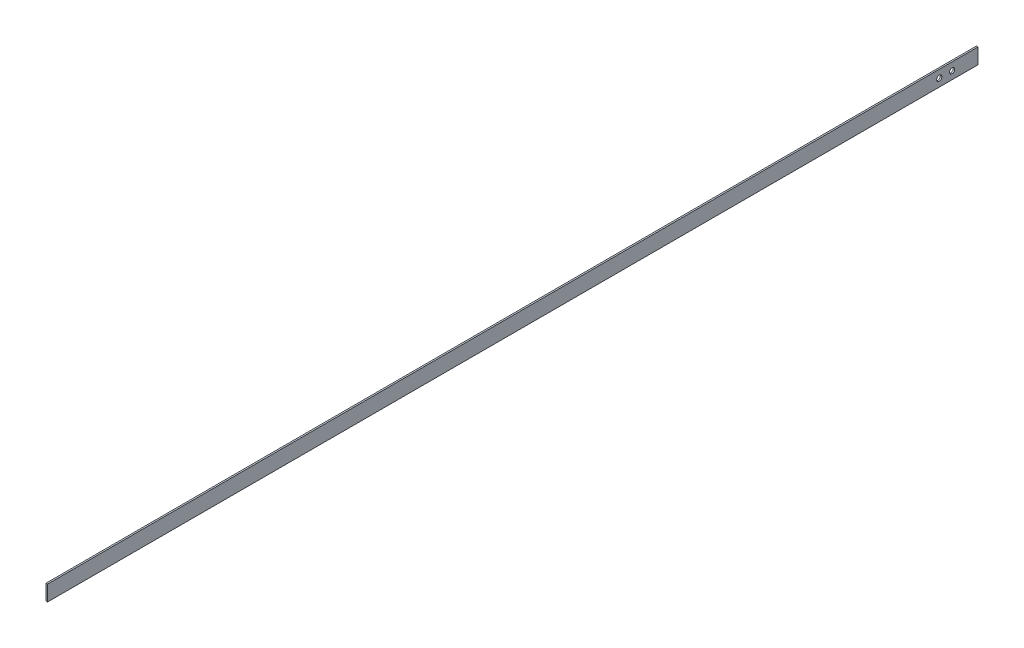
SolidWorks part; units mm, degrees
material "Bellirium COpper"
ref_plane "Front Plane" through (0, 0, 0) normal (0, 0, 1) x (1, 0, 0)
ref_plane "Top Plane" through (0, 0, 0) normal (0, 1, 0) x (1, 0, 0)
ref_plane "Right Plane" through (0, 0, 0) normal (1, 0, 0) x (0, 0, -1)
sketch "Sketch1" plane through (0, 0, 0) normal (0, 0, 1) x (1, 0, 0)
  line L1 (-0.15, -1.5) -> (0.15, -1.5)
  line L2 (-0.15, -1.5) -> (-0.15, 1.5)
  line L3 (-0.15, 1.5) -> (0.15, 1.5)
  line L4 (0.15, -1.5) -> (0.15, 1.5)
  line L5 (-0.15, -1.5) -> (0.15, 1.5) construction
  line L6 (-0.15, 1.5) -> (0.15, -1.5) construction
  point P0 (0, 0)
  dimension "D1" = 0.3
  dimension "D2" = 3
extrude "Boss-Extrude1" add sketch "Sketch1" along normal blind 180
hole_wizard "Ø1.0 (1) Diameter Hole1" positions "Sketch3" profile "Sketch2" hole size "Ø1.0" standard "ISO" end condition through all
sketch "Sketch3" plane through (0.15, 0, 0) normal (1, 0, 0) x (0, 0, -1)
  line L0 (-180, 1.5) -> (0, 1.5) construction
  line L1 (0, 1.5) -> (0, -1.5) construction
  point P0 (-7.5, 0)
  point P2 (-5, 0)
  dimension "D1" = 1.5
  dimension "D2" = 1.5
  dimension "D3" = 2.5
  dimension "D4" = 5
sketch "Sketch2" plane through (0.15, 0, 7.5) normal (0, 1, 0) x (0, 0, -1)
  line L0 (0, 0) -> (0, 0.3)
  line L1 (0, 0.3) -> (0.5, 0.3)
  line L2 (0.5, 0.3) -> (0.5, 0)
  line L5 (0.5, 0) -> (0, 0)
  line L11 (0, -6.35) -> (0, 107.95) construction
  dimension "Thru Hole Dia." = 1
  dimension "Thru Hole Depth" = 0.3
